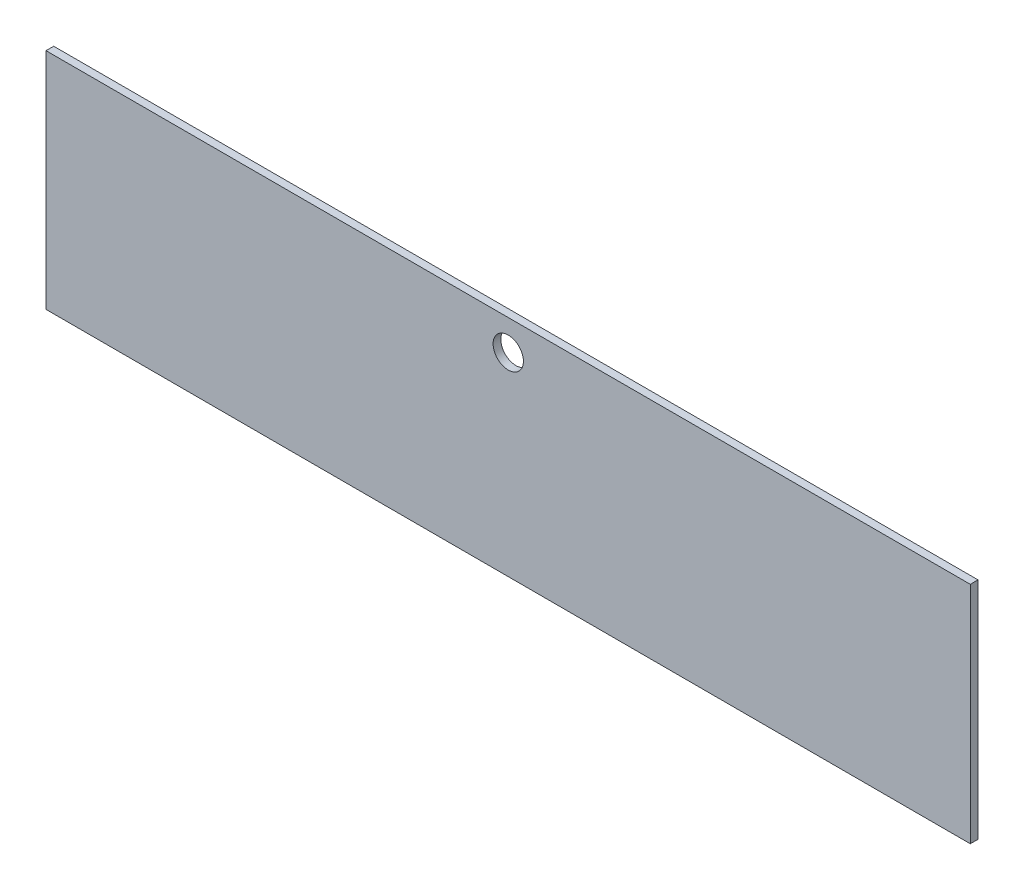
SolidWorks part; units mm, degrees
material "ABS"
ref_plane "Front Plane" through (0, 0, 0) normal (0, 0, 1) x (1, 0, 0)
ref_plane "Top Plane" through (0, 0, 0) normal (0, 1, 0) x (1, 0, 0)
ref_plane "Right Plane" through (0, 0, 0) normal (1, 0, 0) x (0, 0, -1)
sketch "Sketch1" plane through (0, 0, 0) normal (0, 0, 1) x (1, 0, 0)
  line L0 (55, 0) -> (-55, 0) construction
  line L2 (-381.0942, -159.7345) -> (-381.0942, 25)
  line L3 (-381.0942, 25) -> (380.9058, 25)
  line L4 (380.9058, -160.2654) -> (380.9058, 25)
  line L5 (-381.0942, -159.7345) -> (380.9058, -160.2654)
  point P0 (0, 0)
  dimension "D1" = 762
  dimension "D2" = 25
  dimension "D3" = 160
extrude "Boss-Extrude1" add sketch "Sketch1" along normal blind 6.35
sketch "Sketch2" plane through (0, 0, 6.35) normal (0, 0, 1) x (1, 0, 0)
  line L4 (380.9058, -160.2654) -> (380.9058, 25)
  line L5 (380.9058, 25) -> (-381.0942, 25)
  line L6 (-381.0942, 25) -> (-381.0942, -159.7345)
  line L7 (-381.0942, -159.7345) -> (380.9058, -160.2654)
  line L8 (380.9058, -160.2654) -> (380.9058, 25) construction
  line L9 (380.9058, 25) -> (-381.0942, 25) construction
  line L10 (-381.0942, 25) -> (-381.0942, -159.7345) construction
  line L12 (-381.0942, -159.7345) -> (380.9058, -160.2654)
  circle A0 centre (0, 0) radius 12.5
  dimension "D2" = 25
  dimension "D1" = 0
extrude "Cut-Extrude1" cut sketch "Sketch2" against normal through all contours A0
